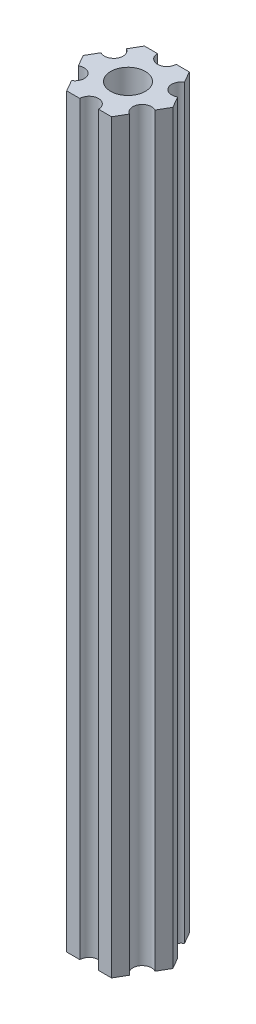
SolidWorks part; units mm, degrees
ref_plane "Plano frontal" through (0, 0, 0) normal (0, 0, 1) x (1, 0, 0)
ref_plane "Plano superior" through (0, 0, 0) normal (0, 1, 0) x (1, 0, 0)
ref_plane "Plano direito" through (0, 0, 0) normal (1, 0, 0) x (0, 0, -1)
ref_plane "Plano1" through (0, 85, 0) normal (0, 1, 0) x (1, 0, 0)
sketch "Esboço1" plane through (0, 85, 0) normal (0, 1, 0) x (1, 0, 0)
  line L0 (6.1627, -1.826) -> (7.2169, 0)
  line L1 (7.2169, 0) -> (6.1627, 1.826)
  line L2 (4.6627, 4.424) -> (3.6084, 6.25)
  line L3 (3.6084, 6.25) -> (1.5, 6.25)
  line L4 (-1.5, 6.25) -> (-3.6084, 6.25)
  line L5 (-3.6084, 6.25) -> (-4.6627, 4.424)
  line L6 (-6.1627, 1.826) -> (-7.2169, 0)
  line L7 (-7.2169, 0) -> (-6.1627, -1.826)
  line L8 (-4.6627, -4.424) -> (-3.6084, -6.25)
  line L9 (-3.6084, -6.25) -> (-1.5, -6.25)
  line L10 (1.5, -6.25) -> (3.6084, -6.25)
  line L11 (3.6084, -6.25) -> (4.6627, -4.424)
  arc A0 (6.1627, 1.826) -> (4.6627, 4.424) centre (5.4127, 3.125) cw
  arc A1 (1.5, 6.25) -> (-1.5, 6.25) centre (0, 6.25) cw
  arc A2 (-4.6627, 4.424) -> (-6.1627, 1.826) centre (-5.4127, 3.125) cw
  arc A3 (-6.1627, -1.826) -> (-4.6627, -4.424) centre (-5.4127, -3.125) cw
  arc A4 (-1.5, -6.25) -> (1.5, -6.25) centre (0, -6.25) cw
  arc A5 (4.6627, -4.424) -> (6.1627, -1.826) centre (5.4127, -3.125) cw
  circle A6 centre (0, 0) radius 2.79
extrude "Ressalto-extrusão1" add sketch "Esboço1" against normal blind 120
